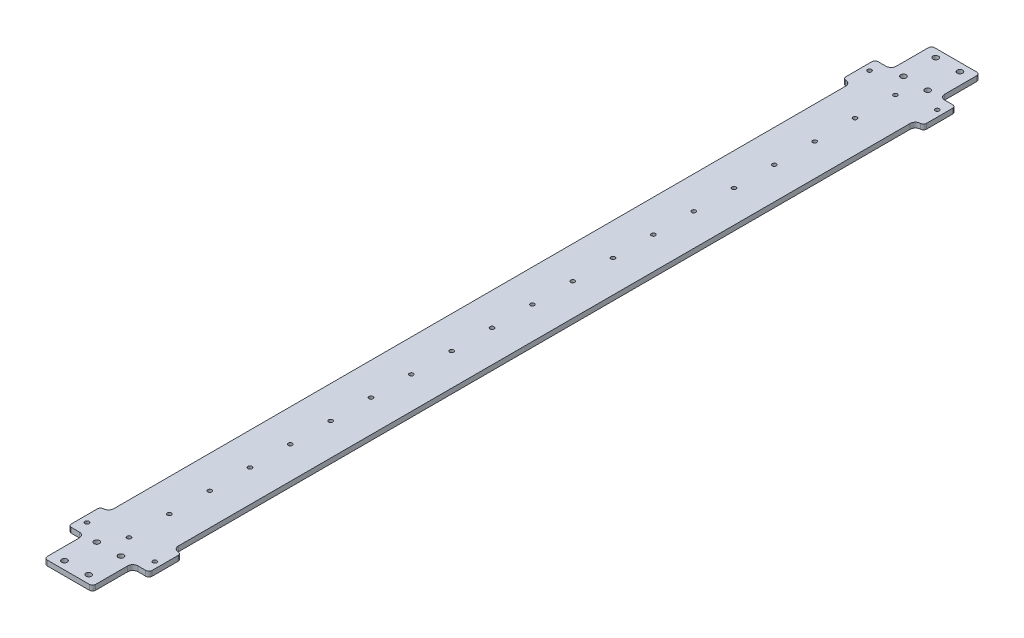
SolidWorks part; units mm, degrees
material "6061-T6 (SS)"
ref_plane "Front Plane" through (0, 0, 0) normal (0, 0, 1) x (1, 0, 0)
ref_plane "Top Plane" through (0, 0, 0) normal (0, 1, 0) x (1, 0, 0)
ref_plane "Right Plane" through (0, 0, 0) normal (1, 0, 0) x (0, 0, -1)
sketch "Sketch2" plane through (0, 0, 0) normal (0, 1, 0) x (1, 0, 0)
  line L0 (-20, 0) -> (20, 0)
  line L1 (25, 250) -> (15, 250)
  line L2 (15, 250) -> (15, 275)
  line L3 (15, 275) -> (-15, 275)
  line L4 (0, 275) -> (0, 0) construction
  line L5 (20, 230) -> (20, 0)
  line L6 (-25, 250) -> (-25, 230)
  line L7 (-15, 250) -> (-15, 275)
  line L8 (-25, 250) -> (-15, 250)
  line L10 (-25, 230) -> (-20, 230)
  line L11 (-20, 230) -> (-20, 0)
  line L12 (25, 230) -> (20, 230)
  line L13 (25, 250) -> (25, 230)
  dimension "D1" = 25
  dimension "D2" = 275
  dimension "D3" = 20
  dimension "D4" = 30
  dimension "D5" = 40
  dimension "D6" = 50
extrude "Boss-Extrude1" add sketch "Sketch2" along normal blind 3.175
fillet "Fillet1" radius 3.175 4 edges at (-15, 1.5875, -250) (15, 1.5875, -250) (20, 1.5875, -230) (-20, 1.5875, -230)
hole_wizard "M3 Clearance Hole1" positions "3DSketch1" profile "Sketch3" hole size "M3" standard "ANSI Metric" end condition through all
sketch3d "3DSketch1"
  line L0 (-15, 3.175, -264.0875) -> (15, 3.175, -264.0875) construction
  line L1 (-15, 3.175, -275) -> (-15, 3.175, -253.175) construction
  line L2 (15, 3.175, -253.175) -> (15, 3.175, -275) construction
  line L3 (0, 3.175, -275) -> (0, 3.175, 0) construction
  line L4 (15, 3.175, -275) -> (-15, 3.175, -275) construction
  line L6 (-7.381, 3.175, -270) -> (7.619, 3.175, -270) construction
  line L7 (7.619, 3.175, -270) -> (7.619, 3.175, -250) construction
  line L8 (7.619, 3.175, -250) -> (-7.381, 3.175, -250) construction
  line L9 (-7.381, 3.175, -250) -> (-7.381, 3.175, -270) construction
  line L12 (-20, 3.175, 0) -> (20, 3.175, 0) construction
  point P14 (-7.381, 3.175, -270)
  point P16 (-7.381, 3.175, -250)
  point P18 (7.619, 3.175, -270)
  point P20 (7.619, 3.175, -250)
  dimension "D1" = 15
  dimension "D2" = 5
  dimension "D3" = 20
sketch "Sketch3" plane through (-7.381, 3.175, -270) normal (1, 0, 0) x (0, 0, 1)
  line L0 (0, 0) -> (0, 3.175)
  line L1 (0, 3.175) -> (1.7, 3.175)
  line L2 (1.7, 3.175) -> (1.7, 0)
  line L5 (1.7, 0) -> (0, 0)
  line L11 (0, -6.35) -> (0, 107.95) construction
  dimension "Thru Hole Dia." = 3.4
  dimension "Thru Hole Depth" = 3.175
fillet "Fillet2" radius 2 6 edges at (-25, 1.5875, -250) (15, 1.5875, -275) (-15, 1.5875, -275) (-25, 1.5875, -230) (25, 1.5875, -230) (25, 1.5875, -250)
hole_wizard "Tap Drill for M3x0.5 Tap1" positions "3DSketch2" profile "Sketch4" hole size "M3x0.5" standard "ANSI Metric" end condition through all
sketch3d "3DSketch2"
  line L3 (-7.381, 3.175, -250) -> (7.619, 3.175, -250) construction
  line L4 (-7.381, 0, -250) -> (-7.381, 3.175, -250) construction
  line L5 (7.619, 0, -250) -> (7.619, 3.175, -250) construction
  line L6 (0.119, 3.175, -250) -> (0, 3.175, 0) construction
  line L9 (-20, 3.175, 0) -> (20, 3.175, 0) construction
  point P0 (0.113, 3.175, -237.5)
  dimension "D1" = 12.5
sketch "Sketch4" plane through (0.113, 3.175, -237.5) normal (1, 0, 0) x (0, 0, 1)
  line L0 (0, 0) -> (0, 3.175)
  line L1 (0, 3.175) -> (1.25, 3.175)
  line L2 (1.25, 3.175) -> (1.25, 0)
  line L5 (1.25, 0) -> (0, 0)
  line L11 (0, -6.35) -> (0, 107.95) construction
  dimension "Thru Hole Dia." = 2.5
  dimension "Thru Hole Depth" = 3.175
pattern_linear "LPattern1" count 10 spacing 25 along (0, 0, 1) of "Tap Drill for M3x0.5 Tap1"
hole_wizard "Tap Drill for M3x0.5 Tap2" positions "3DSketch3" profile "Sketch5" hole size "M3x0.5" standard "ANSI Metric"
sketch3d "3DSketch3"
  line L0 (-7.381, 3.175, -270) -> (7.619, 3.175, -270) construction
  line L1 (-7.381, 0, -270) -> (-7.381, 3.175, -270) construction
  line L2 (7.619, 0, -270) -> (7.619, 3.175, -270) construction
  line L3 (0.119, 3.175, -270) -> (0.113, 3.175, -237.5) construction
  line L4 (0.113, 0, -237.5) -> (0.113, 3.175, -237.5) construction
  line L5 (-20.886, 3.175, -242.5) -> (21.114, 3.175, -242.5) construction
  circle A0 centre (-7.381, 3.175, -250) radius 1.7 construction
  point P0 (-20.886, 3.175, -242.5)
  point P2 (21.114, 3.175, -242.5)
  point P21 (0.114, 3.175, -242.5)
  point P27 (-7.381, 4.875, -250)
  dimension "D2" = 7.5
  dimension "D1" = 42
sketch "Sketch5" plane through (-20.886, 3.175, -242.5) normal (1, 0, 0) x (0, 0, 1)
  line L0 (0, 0) -> (0, 3.175)
  line L1 (0, 3.175) -> (1.25, 3.175)
  line L2 (1.25, 3.175) -> (1.25, 0)
  line L5 (1.25, 0) -> (0, 0)
  line L11 (0, -6.35) -> (0, 107.95) construction
  dimension "Thru Hole Dia." = 2.5
  dimension "Thru Hole Depth" = 3.175
mirror "Mirror1" about plane through (0, 0, 0) normal (0, 0, 1) of "Tap Drill for M3x0.5 Tap2", "Boss-Extrude1", "Fillet1", "M3 Clearance Hole1", "Fillet2", "Tap Drill for M3x0.5 Tap1", "LPattern1"
